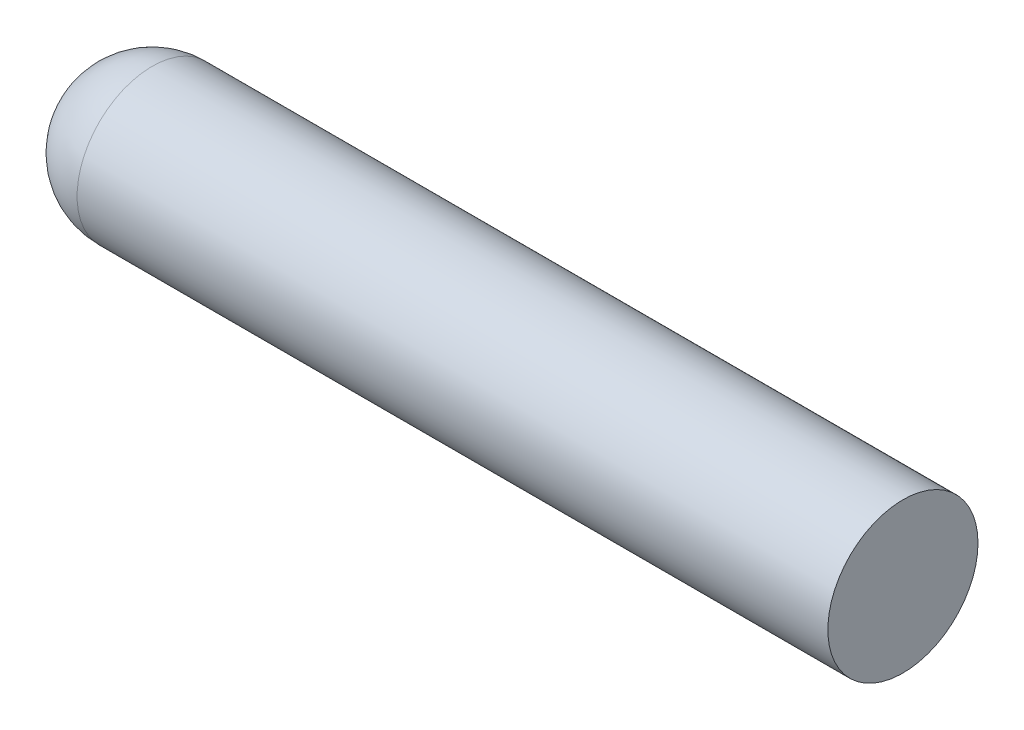
SolidWorks part; units mm, degrees
ref_plane "Front Plane" through (0, 0, 0) normal (0, 0, 1) x (1, 0, 0)
ref_plane "Top Plane" through (0, 0, 0) normal (0, 1, 0) x (1, 0, 0)
ref_plane "Right Plane" through (0, 0, 0) normal (1, 0, 0) x (0, 0, -1)
sketch "Sketch2" plane through (0, 0, 0) normal (0, 1, 0) x (1, 0, 0)
  line L0 (0, 0) -> (-25.4, 0)
  line L1 (-25.4, 0) -> (-25.4, 2.54) construction
  line L3 (0, 2.54) -> (0, 0)
  line L4 (0, 2.54) -> (-27.94, 2.54)
  arc A1 (-27.94, 2.54) -> (-25.4, 0) centre (-25.4, 2.54) ccw
  dimension "D1" = 25.4
  dimension "D2" = 2.54
  dimension "D3" = 2.54
revolve "Revolve4" add sketch "Sketch2" angle 360 about L4
